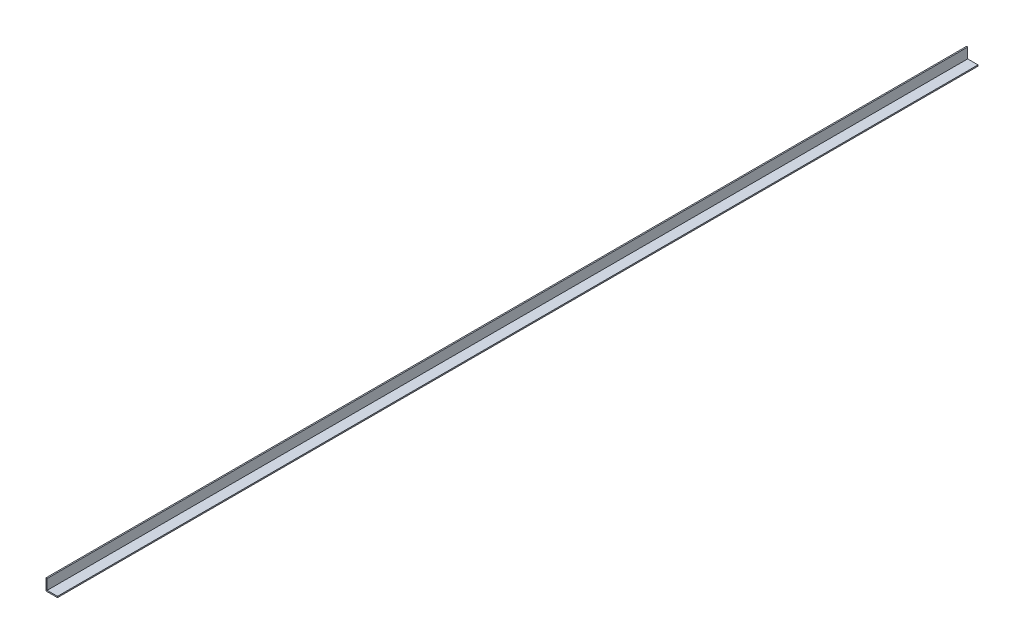
SolidWorks part; units mm, degrees
material "ASTM A36 Acero"
ref_plane "Alzado" through (0, 0, 0) normal (0, 0, 1) x (1, 0, 0)
ref_plane "Planta" through (0, 0, 0) normal (0, 1, 0) x (1, 0, 0)
ref_plane "Vista lateral" through (0, 0, 0) normal (1, 0, 0) x (0, 0, -1)
sketch "Croquis1" plane through (0, 0, 0) normal (0, 0, 1) x (1, 0, 0)
  line L0 (0, 76.2) -> (0, 0)
  line L1 (0, 0) -> (76.2, 0)
  line L2 (76.2, 0) -> (76.2, 7.94)
  line L3 (76.2, 7.94) -> (7.94, 7.94)
  line L4 (7.94, 7.94) -> (7.94, 76.2)
  line L5 (7.94, 76.2) -> (0, 76.2)
  dimension "D1" = 7.94
  dimension "D2" = 76.2
extrude "Saliente-Extruir1" add sketch "Croquis1" against normal blind 6100
